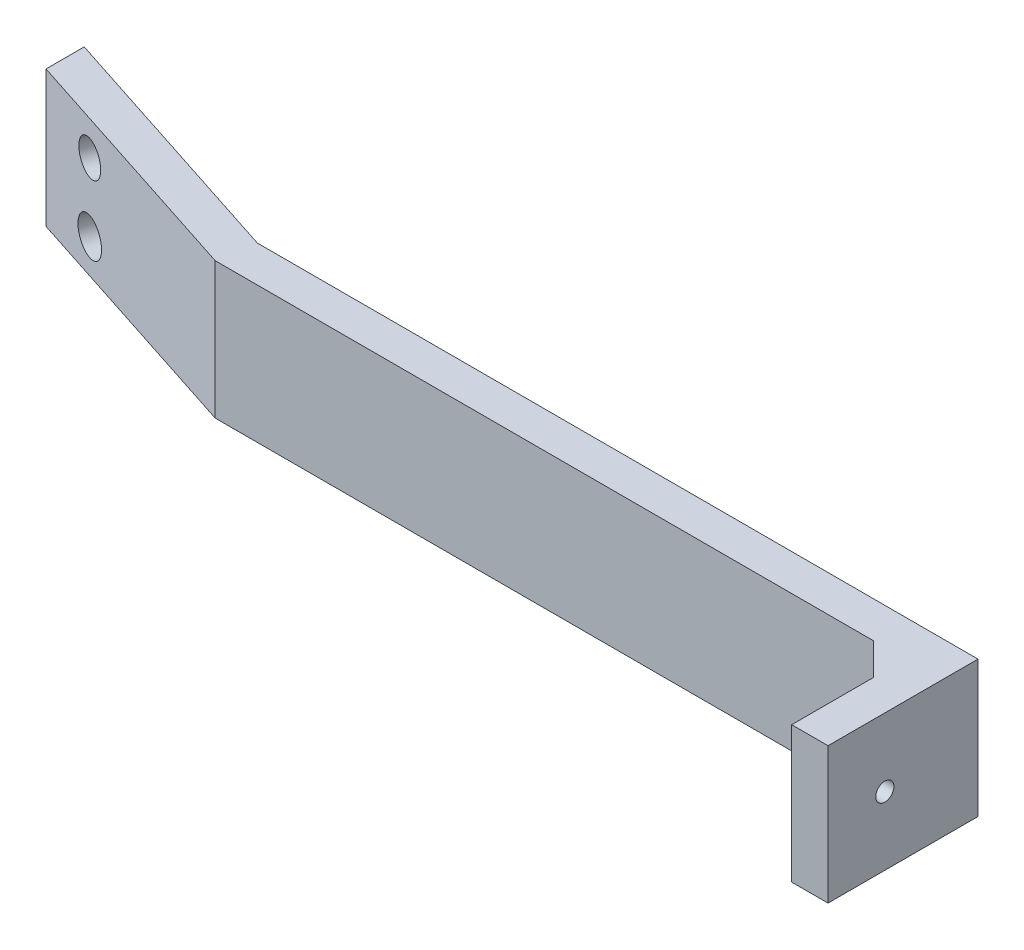
SolidWorks part; units mm, degrees
ref_plane "Front Plane" through (0, 0, 0) normal (0, 0, 1) x (1, 0, 0)
ref_plane "Top Plane" through (0, 0, 0) normal (0, 1, 0) x (1, 0, 0)
ref_plane "Right Plane" through (0, 0, 0) normal (1, 0, 0) x (0, 0, -1)
sketch "Sketch5" plane through (0, 0, 0) normal (0, 0, 1) x (1, 0, 0)
  line L1 (-107.5, 15) -> (107.5, 15)
  line L2 (-107.5, 15) -> (-107.5, -15)
  line L3 (-107.5, -15) -> (107.5, -15)
  line L4 (107.5, 15) -> (107.5, -15)
  line L5 (-107.5, 15) -> (107.5, -15) construction
  line L6 (-107.5, -15) -> (107.5, 15) construction
  point P0 (0, 0)
  dimension "D1" = 215
  dimension "D2" = 30
extrude "Boss-Extrude3" add sketch "Sketch5" along normal blind 50
sketch "Sketch6" plane through (0, 15, 0) normal (0, 1, 0) x (1, 0, 0)
  line L0 (-107.5, -32.077) -> (-52.3387, -50)
  line L1 (-107.5, -50) -> (-107.5, 0) construction
  line L2 (107.5, -50) -> (-107.5, -50) construction
  line L3 (-107.5, -50) -> (-52.3387, -50)
  line L4 (-107.5, -32.077) -> (-107.5, -50)
  dimension "D1" = 162
  dimension "D2" = 58
extrude "Cut-Extrude2" cut sketch "Sketch6" against normal through all
sketch "Sketch7" plane through (0, 15, 0) normal (0, 1, 0) x (1, 0, 0)
  line L0 (107.5, -42) -> (-51.0716, -42)
  line L1 (107.5, -50) -> (107.5, 0) construction
  line L2 (107.5, -50) -> (-52.3387, -50) construction
  line L3 (-107.5, -23.6653) -> (-51.0716, -42)
  line L4 (-107.5, -32.077) -> (-107.5, 0) construction
  line L5 (-52.3387, -50) -> (-107.5, -32.077) construction
  line L6 (-107.5, -23.6653) -> (-107.5, 0)
  line L7 (-107.5, 0) -> (107.5, 0)
  line L8 (107.5, 0) -> (107.5, -42)
  dimension "D1" = 8
  dimension "D2" = 8
extrude "Cut-Extrude3" cut sketch "Sketch7" against normal through all
sketch "Sketch8" plane through (0, 0, 50) normal (0, 0, 1) x (1, 0, 0)
  line L0 (-52.3387, -15) -> (107.5, -15) construction
  line L1 (107.5, 15) -> (99.5, 15)
  line L2 (107.5, 15) -> (107.5, -15)
  line L3 (107.5, -15) -> (99.5, -15)
  line L4 (99.5, 15) -> (99.5, -15)
  dimension "D1" = 8
extrude "Boss-Extrude4" add sketch "Sketch8" along normal blind 25
sketch "Sketch9" plane through (99.5, 0, 0) normal (-1, 0, 0) x (0, 0, 1)
  line L1 (50, -15) -> (57, -15)
  line L2 (50, -15) -> (50, -10)
  line L3 (50, -10) -> (57, -10)
  line L4 (57, -15) -> (57, -10)
  line L5 (50, 15) -> (57, 15)
  line L6 (50, 15) -> (50, 10)
  line L7 (50, 10) -> (57, 10)
  line L8 (57, 15) -> (57, 10)
  dimension "D1" = 5
  dimension "D2" = 5
  dimension "D3" = 7
  dimension "D4" = 7
extrude "Boss-Extrude5" add sketch "Sketch9" along normal blind 7
sketch "Sketch10" plane through (0, -15, 0) normal (0, -1, 0) x (1, 0, 0)
  line L0 (92.5, 50) -> (99.5, 57)
  line L1 (99.5, 57) -> (92.5, 57)
  line L2 (92.5, 57) -> (92.5, 50)
extrude "Cut-Extrude4" cut sketch "Sketch10" against normal through all
sketch "Sketch11" plane through (99.5, 0, 0) normal (-1, 0, 0) x (0, 0, 1)
  line L4 (75, 15) -> (57, 15) construction
  line L5 (75, 15) -> (75, -15) construction
  circle A0 centre (62.5, 0) radius 2
  dimension "D1" = 4
  dimension "D2" = 15
  dimension "D3" = 12.5
extrude "Cut-Extrude5" cut sketch "Sketch11" against normal through all
sketch "Sketch12" plane through (-19.6925, 0, 60.6074) normal (-0.309, 0, 0.9511) x (0.9511, 0, 0.309)
  line L0 (-92.3262, -15) -> (-92.3262, 15) construction
  line L1 (-34.3262, -15) -> (-92.3262, -15) construction
  circle A0 centre (-77.3262, 7.5) radius 3.7401
  circle A1 centre (-77.3262, -7.5) radius 4.0342
  dimension "D1" = 15
  dimension "D2" = 15
  dimension "D3" = 15
  dimension "D4" = 7.5
extrude "Cut-Extrude6" cut sketch "Sketch12" against normal through all
